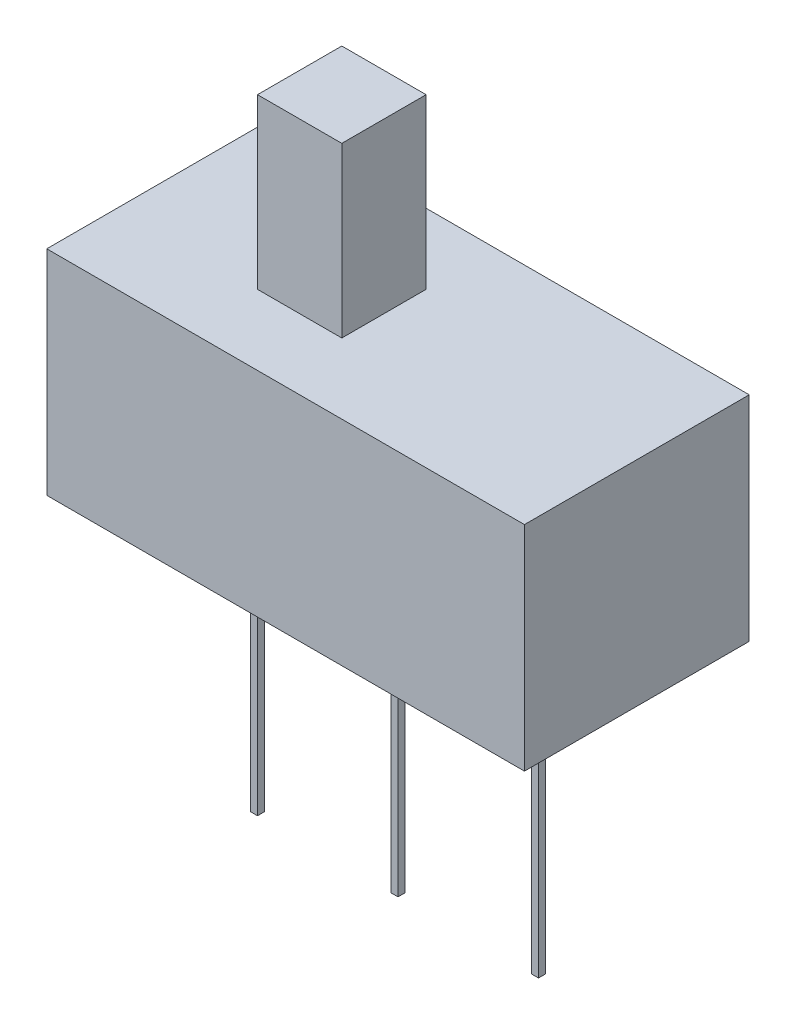
SolidWorks part; units mm, degrees
material "Alumina"
ref_plane "Front" through (0, 0, 0) normal (0, 0, 1) x (1, 0, 0)
ref_plane "Top" through (0, 0, 0) normal (0, 1, 0) x (1, 0, 0)
ref_plane "Right" through (0, 0, 0) normal (1, 0, 0) x (0, 0, -1)
sketch "Sketch1" plane through (0, 0, 0) normal (0, 0, 1) x (1, 0, 0)
  line L1 (-4.25, 1.9) -> (4.25, 1.9)
  line L2 (-4.25, 1.9) -> (-4.25, -1.9)
  line L3 (-4.25, -1.9) -> (4.25, -1.9)
  line L4 (4.25, 1.9) -> (4.25, -1.9)
  line L5 (-4.25, 1.9) -> (4.25, -1.9) construction
  line L6 (-4.25, -1.9) -> (4.25, 1.9) construction
  point P0 (0, 0)
  dimension "D1" = 8.5
  dimension "D2" = 3.8
extrude "Boss-Extrude1" add sketch "Sketch1" along normal mid plane 4
sketch "Sketch2" plane through (0, 1.9, 0) normal (0, 1, 0) x (1, 0, 0)
  line L0 (-4.25, -2) -> (-4.25, 2) construction
  line L1 (-1.75, 0.75) -> (-0.25, 0.75)
  line L2 (-1.75, 0.75) -> (-1.75, -0.75)
  line L3 (-1.75, -0.75) -> (-0.25, -0.75)
  line L4 (-0.25, 0.75) -> (-0.25, -0.75)
  line L5 (-1.75, 0.75) -> (-0.25, -0.75) construction
  line L6 (-1.75, -0.75) -> (-0.25, 0.75) construction
  point P0 (-1, 0)
  point P7 (0, 0)
  dimension "D1" = 1.5
  dimension "D2" = 4
extrude "Boss-Extrude2" add sketch "Sketch2" along normal blind 3
sketch "Sketch3" plane through (0, -1.9, 0) normal (0, -1, 0) x (1, 0, 0)
  line L1 (-0.0625, 0.0625) -> (0.0625, 0.0625)
  line L2 (-0.0625, 0.0625) -> (-0.0625, -0.0625)
  line L3 (-0.0625, -0.0625) -> (0.0625, -0.0625)
  line L4 (0.0625, 0.0625) -> (0.0625, -0.0625)
  line L5 (-0.0625, 0.0625) -> (0.0625, -0.0625) construction
  line L6 (-0.0625, -0.0625) -> (0.0625, 0.0625) construction
  line L7 (-2.5625, 0.0625) -> (-2.4375, 0.0625)
  line L8 (-2.5625, 0.0625) -> (-2.5625, -0.0625)
  line L9 (-2.5625, -0.0625) -> (-2.4375, -0.0625)
  line L10 (-2.4375, 0.0625) -> (-2.4375, -0.0625)
  line L11 (-2.5625, 0.0625) -> (-2.4375, -0.0625) construction
  line L12 (-2.5625, -0.0625) -> (-2.4375, 0.0625) construction
  line L13 (2.4375, 0.0625) -> (2.5625, 0.0625)
  line L14 (2.4375, 0.0625) -> (2.4375, -0.0625)
  line L15 (2.4375, -0.0625) -> (2.5625, -0.0625)
  line L16 (2.5625, 0.0625) -> (2.5625, -0.0625)
  line L17 (2.4375, 0.0625) -> (2.5625, -0.0625) construction
  line L18 (2.4375, -0.0625) -> (2.5625, 0.0625) construction
  point P0 (0, 0)
  point P5 (2.5, 0)
  point P8 (-2.5, 0)
  point P16 (0.2641, -0.001)
  point P17 (0, 0)
  dimension "D1" = 0.125
  dimension "D2" = 2.5
  dimension "D3" = 2.5
extrude "Boss-Extrude3" add sketch "Sketch3" along normal blind 5
